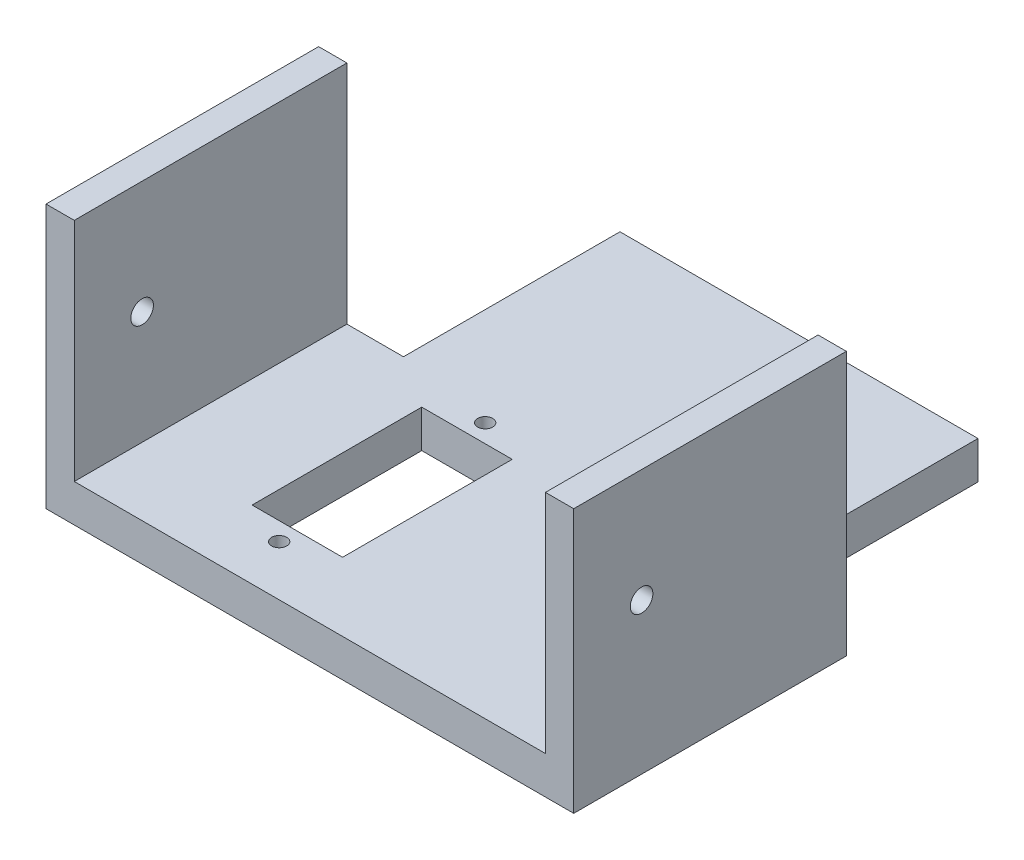
SolidWorks part; units mm, degrees
ref_plane "Front Plane" through (0, 0, 0) normal (0, 0, 1) x (1, 0, 0)
ref_plane "Top Plane" through (0, 0, 0) normal (0, 1, 0) x (1, 0, 0)
ref_plane "Right Plane" through (0, 0, 0) normal (1, 0, 0) x (0, 0, -1)
sketch "Sketch1" plane through (0, 0, 0) normal (0, 1, 0) x (1, 0, 0)
  line L1 (-35, 75) -> (35, 75)
  line L2 (-35, 75) -> (-35, -75)
  line L3 (-35, -75) -> (35, -75)
  line L4 (35, 75) -> (35, -75)
  line L5 (-35, 75) -> (35, -75) construction
  line L6 (-35, -75) -> (35, 75) construction
  point P0 (0, 0)
  dimension "D1" = 70
  dimension "D2" = 150
extrude "Boss-Extrude1" add sketch "Sketch1" along normal blind 5
sketch "Sketch7" plane through (0, 0, -75) normal (0, 0, -1) x (-1, 0, 0)
  line L0 (0, -3.3645) -> (0, 45.0062) construction
  line L1 (-35, 5) -> (-31.25, 5)
  line L2 (-35, 5) -> (-35, 35)
  line L3 (-35, 35) -> (-31.25, 35)
  line L4 (-31.25, 5) -> (-31.25, 35)
  line L5 (35, 35) -> (31.25, 35)
  line L6 (31.25, 5) -> (31.25, 35)
  line L7 (35, 5) -> (31.25, 5)
  line L8 (35, 5) -> (35, 35)
  dimension "D1" = 30
  dimension "D2" = 62.5
extrude "Boss-Extrude2" add sketch "Sketch7" against normal blind 90
sketch "Sketch9" plane through (0, 0, 0) normal (0, -1, 0) x (1, 0, 0)
  line L0 (10.75, 0) -> (10.75, -40) construction
  line L1 (-10.75, 0) -> (-10.75, -40) construction
  circle A0 centre (-10.75, 0) radius 10 construction
  circle A1 centre (10.75, 0) radius 10 construction
  dimension "D1" = 20
  dimension "D2" = 20
  dimension "D3" = 21.5
  dimension "D4" = 10.75
  dimension "D5" = 40
sketch "Sketch10" plane through (35, 0, 0) normal (1, 0, 0) x (0, 0, -1)
  line L1 (-15, 5) -> (-75, 5)
  line L2 (-15, 5) -> (-15, 0)
  line L3 (-15, 0) -> (-75, 0)
  line L4 (-75, 5) -> (-75, 0)
extrude "Cut-Extrude2" cut sketch "Sketch10" against normal blind 75
sketch "Sketch11" plane through (-35, 0, 0) normal (-1, 0, 0) x (0, 0, 1)
  line L0 (15, 0) -> (15, 35) construction
  circle A0 centre (6, 20) radius 1.5
  dimension "D3" = 3
  dimension "D1" = 9
  dimension "D2" = 15
extrude "Cut-Extrude3" cut sketch "Sketch11" against normal blind 75
sketch "Sketch12" plane through (0, 0, 0) normal (0, -1, 0) x (1, 0, 0)
  line L0 (35, -21.1622) -> (23.7455, -21.1622)
  line L1 (35, 15) -> (35, -75) construction
  line L2 (23.7455, -21.1622) -> (23.7455, -49.8787)
  line L3 (35, -75) -> (-35, -75) construction
  line L4 (0, 15) -> (0, -80.0295) construction
  line L5 (35, 15) -> (-35, 15) construction
  line L7 (-35, -21.1622) -> (-23.7455, -21.1622)
  line L8 (-35, -21.1622) -> (-35, -75)
  line L9 (-35, -75) -> (-23.7455, -75)
  line L10 (23.7455, -75) -> (35, -75)
  line L11 (23.7455, -49.8787) -> (-23.7455, -49.8787)
  line L12 (-23.7455, -49.8787) -> (-23.7455, -21.1622)
  line L13 (-35, -21.1622) -> (-35, -75)
  line L14 (-23.7455, -75) -> (23.7455, -75)
  line L15 (35, -75) -> (35, -21.1622)
  line M8 (35, -75) -> (35, 15)
  line M10 (-35, 15) -> (-35, -75)
  line M11 (-35, -75) -> (35, -75)
extrude "Cut-Extrude4" cut sketch "Sketch12" against normal blind 40 contours L11 L4 L14 L0 L2 M11 M8 | L4 L11 L12 L7 M10 M11
sketch "Sketch13" plane through (0, 0, 0) normal (0, -1, 0) x (1, 0, 0)
  line L1 (-16.75, 5.91) -> (-4.75, 5.91)
  line L2 (-16.75, 5.91) -> (-16.75, -16.59)
  line L3 (-16.75, -16.59) -> (-4.75, -16.59)
  line L4 (-4.75, 5.91) -> (-4.75, -16.59)
  line L5 (-16.75, 5.91) -> (-4.75, -16.59) construction
  line L6 (-16.75, -16.59) -> (-4.75, 5.91) construction
  circle A1 centre (-10.75, 8.32) radius 1
  circle A2 centre (-10.75, -19) radius 1
  point P0 (-10.75, -5.34)
  point P5 (-10.75, 5.91)
  point P6 (-10.75, -16.59)
  dimension "D5" = 2
  dimension "D1" = 22.5
  dimension "D2" = 12
  dimension "D4" = 2.41
  dimension "D6" = 2.41
extrude "Cut-Extrude5" cut sketch "Sketch13" against normal blind 35
